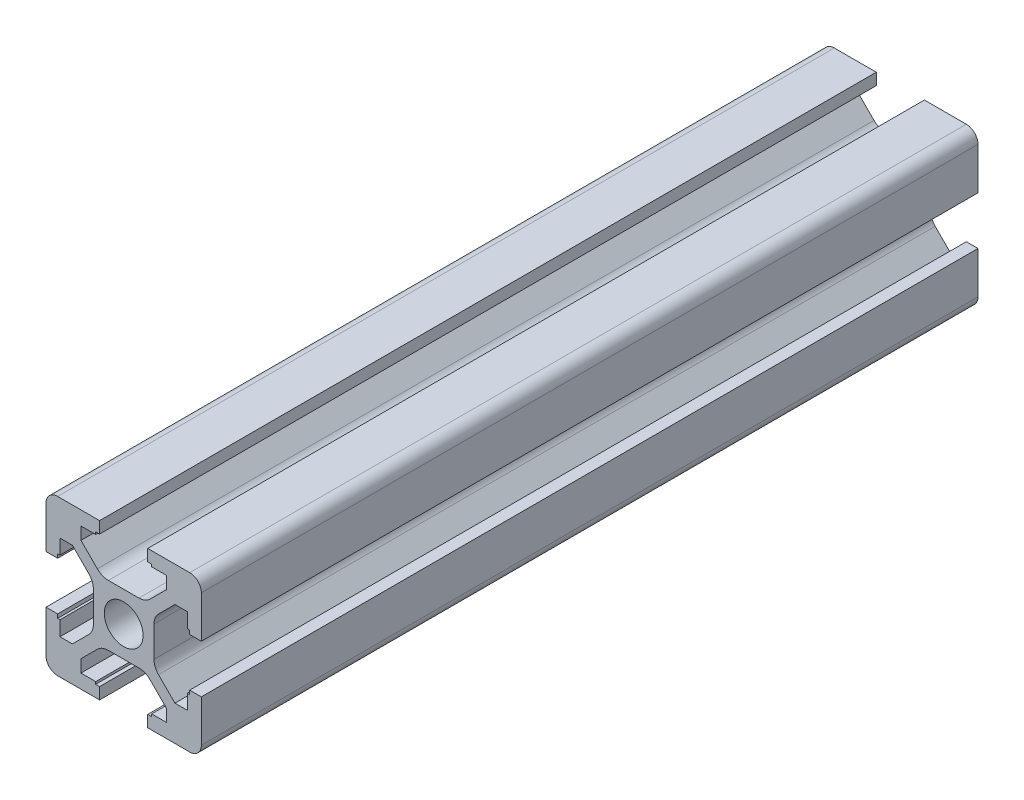
SolidWorks part; units mm, degrees
material "6063-T5"
ref_plane "Front Plane" through (0, 0, 0) normal (0, 0, 1) x (1, 0, 0)
ref_plane "Top Plane" through (0, 0, 0) normal (0, 1, 0) x (1, 0, 0)
ref_plane "Right Plane" through (0, 0, 0) normal (1, 0, 0) x (0, 0, -1)
sketch "Sketch1" plane through (0, 0, 0) normal (0, 0, 1) x (1, 0, 0)
  line L0 (0, 0) -> (0, 15) construction
  line L1 (-10, 10) -> (0, 10) construction
  line L2 (-10, 10) -> (-10, 0) construction
  line L3 (1.9716, 3.9) -> (-1.9716, 3.9)
  line L4 (-3.3858, 4.4858) -> (-5.5, 6.6)
  line L5 (0, 0) -> (-15, 0) construction
  line L6 (-5.5, 6.6) -> (-5.5, 8.2)
  line L7 (-5.5, 8.2) -> (-3.6, 8.2)
  line L8 (-3.6, 8.2) -> (-3.6, 8.5)
  line L9 (-3.6, 8.5) -> (-3.1, 8.5)
  line L10 (-3.1, 8.5) -> (-3.1, 10)
  line L11 (-3.1, 10) -> (-8.5, 10)
  line L12 (-10, 8.5) -> (-10, 3.1)
  line L13 (-10, 3.1) -> (-8.5, 3.1)
  line L14 (-8.5, 3.1) -> (-8.5, 3.6)
  line L15 (-8.5, 3.6) -> (-8.2, 3.6)
  line L16 (-8.2, 3.6) -> (-8.2, 5.5)
  line L17 (-8.2, 5.5) -> (-6.6, 5.5)
  line L18 (-6.6, 5.5) -> (-4.4858, 3.3858)
  line L19 (-3.9, 1.9716) -> (-3.9, -1.9716)
  line L20 (3.9, 1.9716) -> (3.9, -1.9716)
  line L21 (6.6, 5.5) -> (4.4858, 3.3858)
  line L22 (8.2, 5.5) -> (6.6, 5.5)
  line L23 (8.2, 3.6) -> (8.2, 5.5)
  line L24 (8.5, 3.6) -> (8.2, 3.6)
  line L25 (8.5, 3.1) -> (8.5, 3.6)
  line L26 (10, 3.1) -> (8.5, 3.1)
  line L27 (10, 8.5) -> (10, 3.1)
  line L28 (3.1, 10) -> (8.5, 10)
  line L29 (3.1, 8.5) -> (3.1, 10)
  line L30 (3.6, 8.5) -> (3.1, 8.5)
  line L31 (3.6, 8.2) -> (3.6, 8.5)
  line L32 (5.5, 8.2) -> (3.6, 8.2)
  line L33 (5.5, 6.6) -> (5.5, 8.2)
  line L34 (3.3858, 4.4858) -> (5.5, 6.6)
  line L35 (6.6, -5.5) -> (4.4858, -3.3858)
  line L36 (8.2, -5.5) -> (6.6, -5.5)
  line L37 (8.2, -3.6) -> (8.2, -5.5)
  line L38 (8.5, -3.6) -> (8.2, -3.6)
  line L39 (8.5, -3.1) -> (8.5, -3.6)
  line L40 (10, -3.1) -> (8.5, -3.1)
  line L41 (10, -8.5) -> (10, -3.1)
  line L42 (3.1, -10) -> (8.5, -10)
  line L43 (3.1, -8.5) -> (3.1, -10)
  line L44 (3.6, -8.5) -> (3.1, -8.5)
  line L45 (3.6, -8.2) -> (3.6, -8.5)
  line L46 (5.5, -8.2) -> (3.6, -8.2)
  line L47 (5.5, -6.6) -> (5.5, -8.2)
  line L48 (3.3858, -4.4858) -> (5.5, -6.6)
  line L49 (1.9716, -3.9) -> (-1.9716, -3.9)
  line L50 (-3.3858, -4.4858) -> (-5.5, -6.6)
  line L51 (-5.5, -6.6) -> (-5.5, -8.2)
  line L52 (-5.5, -8.2) -> (-3.6, -8.2)
  line L53 (-3.6, -8.2) -> (-3.6, -8.5)
  line L54 (-3.6, -8.5) -> (-3.1, -8.5)
  line L55 (-3.1, -8.5) -> (-3.1, -10)
  line L56 (-3.1, -10) -> (-8.5, -10)
  line L57 (-10, -8.5) -> (-10, -3.1)
  line L58 (-10, -3.1) -> (-8.5, -3.1)
  line L59 (-8.5, -3.1) -> (-8.5, -3.6)
  line L60 (-8.5, -3.6) -> (-8.2, -3.6)
  line L61 (-8.2, -3.6) -> (-8.2, -5.5)
  line L62 (-8.2, -5.5) -> (-6.6, -5.5)
  line L63 (-6.6, -5.5) -> (-4.4858, -3.3858)
  circle A0 centre (0, 0) radius 2.5
  arc A1 (-10, -8.5) -> (-8.5, -10) centre (-8.5, -8.5) ccw
  arc A2 (8.5, -10) -> (10, -8.5) centre (8.5, -8.5) ccw
  arc A3 (10, 8.5) -> (8.5, 10) centre (8.5, 8.5) ccw
  arc A4 (-8.5, 10) -> (-10, 8.5) centre (-8.5, 8.5) ccw
  arc A5 (-3.3858, -4.4858) -> (-1.9716, -3.9) centre (-1.9716, -5.9) cw
  arc A6 (1.9716, -3.9) -> (3.3858, -4.4858) centre (1.9716, -5.9) cw
  arc A7 (4.4858, -3.3858) -> (3.9, -1.9716) centre (5.9, -1.9716) cw
  arc A8 (3.9, 1.9716) -> (4.4858, 3.3858) centre (5.9, 1.9716) cw
  arc A9 (1.9716, 3.9) -> (3.3858, 4.4858) centre (1.9716, 5.9) ccw
  arc A10 (-1.9716, 3.9) -> (-3.3858, 4.4858) centre (-1.9716, 5.9) cw
  arc A11 (-4.4858, 3.3858) -> (-3.9, 1.9716) centre (-5.9, 1.9716) cw
  arc A12 (-3.9, -1.9716) -> (-4.4858, -3.3858) centre (-5.9, -1.9716) cw
  point P40 (0, 3.9)
  point P41 (3.9, 0)
  point P70 (-3.9, 0)
  point P72 (-10, -10)
  point P75 (10, -10)
  point P78 (10, 10)
  point P84 (-2.8, -3.9)
  point P87 (2.8, -3.9)
  point P90 (3.9, -2.8)
  point P93 (3.9, 2.8)
  point P96 (2.8, 3.9)
  point P99 (-2.8, 3.9)
  point P102 (-3.9, 2.8)
  point P105 (-3.9, -2.8)
  dimension "D3" = 5
  dimension "D14" = 1.5
  dimension "D15" = 2
  dimension "D1" = 10
  dimension "D2" = 10
  dimension "D4" = 15
  dimension "D5" = 5.5
  dimension "D6" = 3.4
  dimension "D7" = 6.1
  dimension "D8" = 6.1
  dimension "D9" = 3.1
  dimension "D10" = 3.6
  dimension "D11" = 1.5556
  dimension "D12" = 1.8
  dimension "D13" = 1.5
extrude "Boss-Extrude1" add sketch "Sketch1" along normal blind 100
